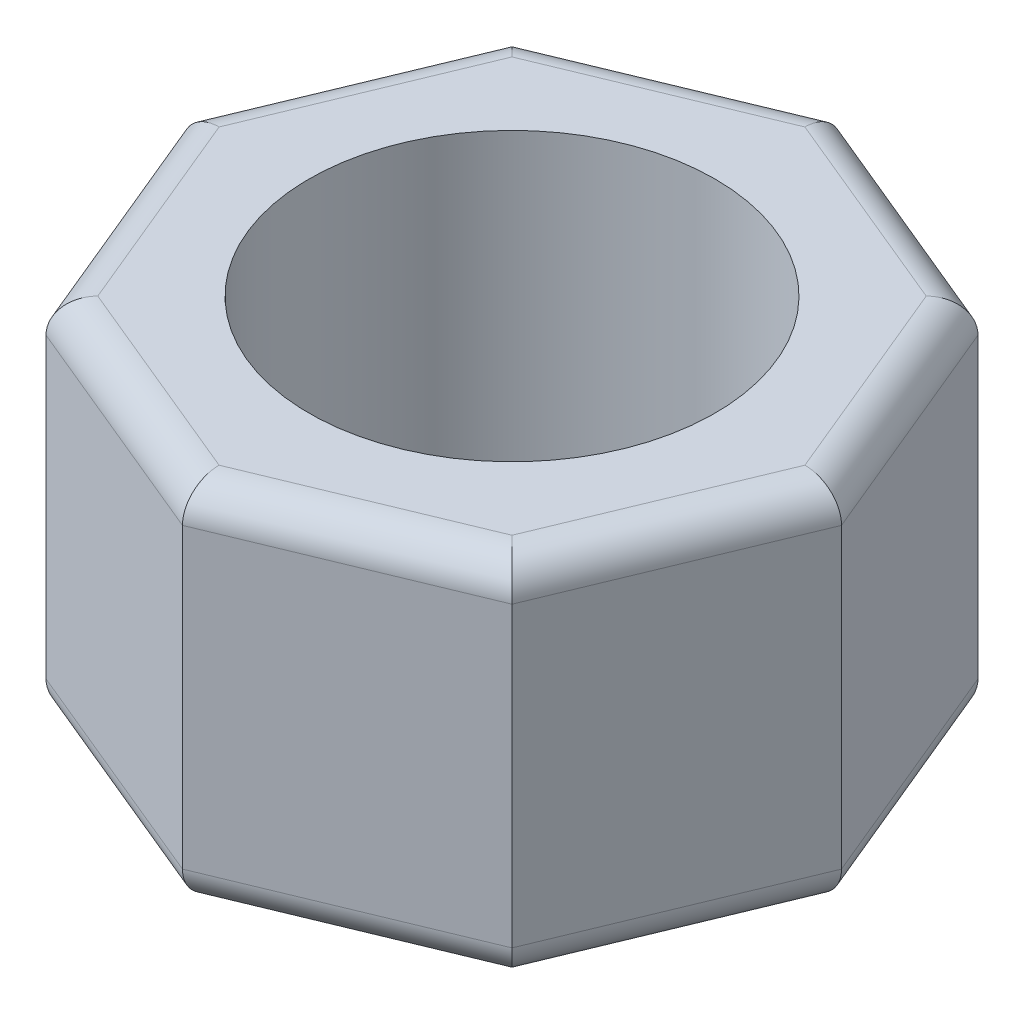
SolidWorks part; units mm, degrees
ref_plane "Front Plane" through (0, 0, 0) normal (0, 0, 1) x (1, 0, 0)
ref_plane "Top Plane" through (0, 0, 0) normal (0, 1, 0) x (1, 0, 0)
ref_plane "Right Plane" through (0, 0, 0) normal (1, 0, 0) x (0, 0, -1)
sketch "Sketch1" plane through (0, 0, 0) normal (0, 1, 0) x (1, 0, 0)
  line L1 (9.7415, 0) -> (6.8883, 6.8883)
  line L2 (6.8883, 6.8883) -> (0, 9.7415)
  line L3 (0, 9.7415) -> (-6.8883, 6.8883)
  line L4 (-6.8883, 6.8883) -> (-9.7415, 0)
  line L5 (-9.7415, 0) -> (-6.8883, -6.8883)
  line L6 (-6.8883, -6.8883) -> (0, -9.7415)
  line L7 (0, -9.7415) -> (6.8883, -6.8883)
  line L8 (6.8883, -6.8883) -> (9.7415, 0)
  circle A0 centre (0, 0) radius 9 construction
  circle A1 centre (0, 0) radius 6
  dimension "D2" = 12
  dimension "D1" = 18
extrude "Boss-Extrude1" add sketch "Sketch1" along normal blind 10.8
fillet "Fillet1" radius 1 16 edges at (3.4442, 10.8, 8.3149) (-3.4442, 10.8, 8.3149) (-8.3149, 10.8, 3.4442) (-8.3149, 10.8, -3.4442) (-3.4442, 10.8, -8.3149) (3.4442, 10.8, -8.3149) (8.3149, 10.8, -3.4442) (8.3149, 10.8, 3.4442) (-8.3149, 0, -3.4442) (-8.3149, 0, 3.4442) (-3.4442, 0, 8.3149) (3.4442, 0, 8.3149) (8.3149, 0, -3.4442) (8.3149, 0, 3.4442) (3.4442, 0, -8.3149) (-3.4442, 0, -8.3149)
